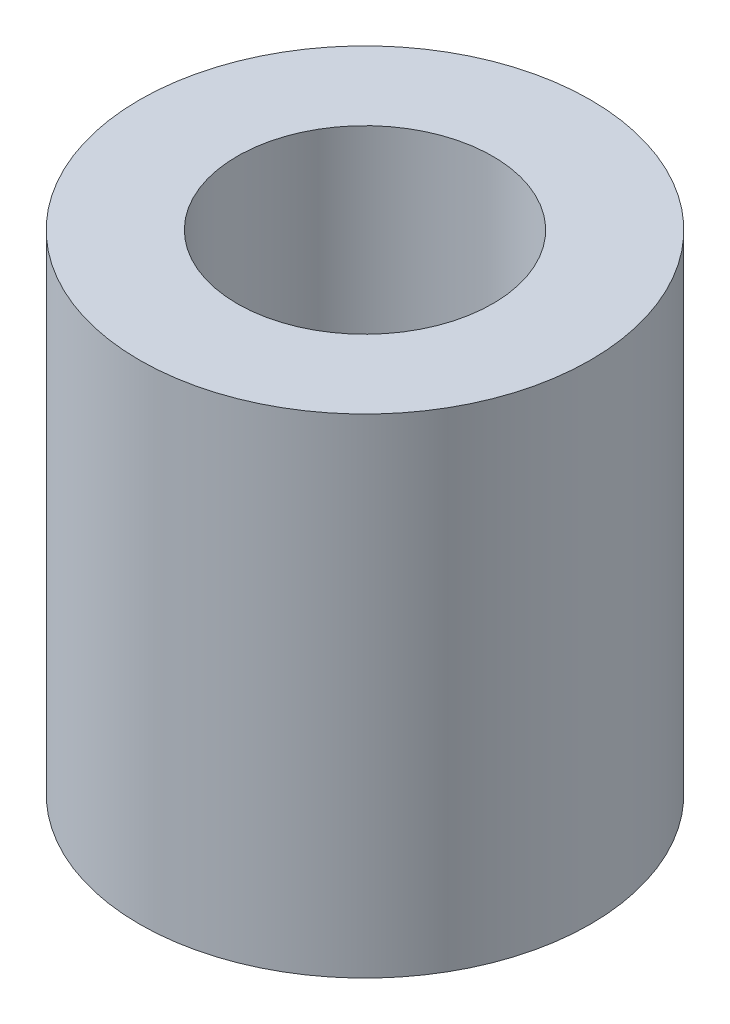
SolidWorks part; units mm, degrees
ref_plane "Front Plane" through (0, 0, 0) normal (0, 0, 1) x (1, 0, 0)
ref_plane "Top Plane" through (0, 0, 0) normal (0, 1, 0) x (1, 0, 0)
ref_plane "Right Plane" through (0, 0, 0) normal (1, 0, 0) x (0, 0, -1)
sketch "Sketch1" plane through (0, 0, 0) normal (0, 1, 0) x (1, 0, 0)
  circle A0 centre (0, 0) radius 3
  dimension "D1" = 6
extrude "Boss-Extrude1" add sketch "Sketch1" along normal mid plane 6.5
hole_wizard "M3 Clearance Hole1" positions "Sketch2" profile "Sketch3" hole size "M3" standard "ISO" end condition through all
sketch "Sketch2" plane through (0, 3.25, 0) normal (0, 1, 0) x (1, 0, 0)
  point P0 (0, 0)
sketch "Sketch3" plane through (0, 3.25, 0) normal (1, 0, 0) x (0, 0, 1)
  line L0 (0, 0) -> (0, 6.5)
  line L1 (0, 6.5) -> (1.7, 6.5)
  line L2 (1.7, 6.5) -> (1.7, 0)
  line L5 (1.7, 0) -> (0, 0)
  line L11 (0, -6.35) -> (0, 107.95) construction
  dimension "Thru Hole Dia." = 3.4
  dimension "Thru Hole Depth" = 6.5
